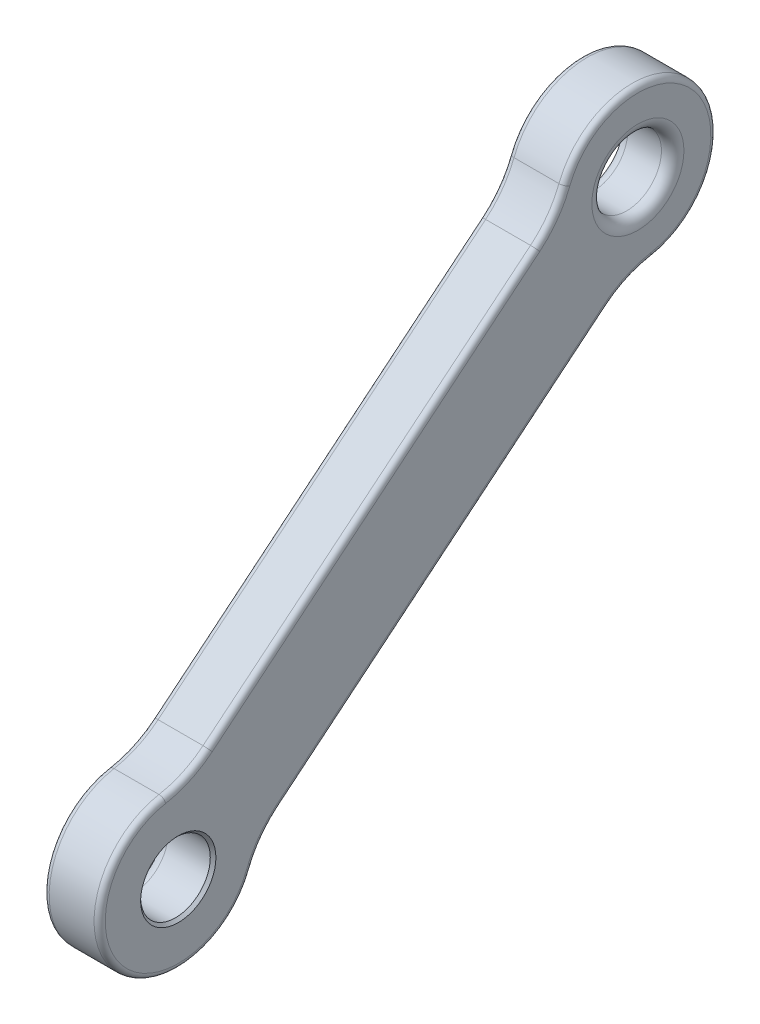
SolidWorks part; units mm, degrees
material "ABS"
ref_plane "Front Plane" through (0, 0, 0) normal (1, 0, 0) x (0, 1, 0)
ref_plane "Top Plane" through (0, 0, 0) normal (0, 0, 1) x (0, 1, 0)
ref_plane "Right Plane" through (0, 0, 0) normal (0, 1, 0) x (-1, 0, 0)
sketch "Sketch1" plane through (0, 0, 0) normal (1, 0, 0) x (0, 1, 0)
  line L0 (-11.6048, -20) -> (24.9519, -20)
  line L1 (84.9519, 40) -> (84.9519, 57.8005)
  line L4 (-38.5328, 56.8878) -> (-47.7982, 43.6554)
  line L5 (64.9519, 37.5) -> (87.5414, -36.1119)
  line L6 (87.5414, -36.1119) -> (67.3498, -81.8536)
  line L7 (67.3498, -81.8536) -> (4.2234, -204.9062)
  line L8 (67.3498, -81.8536) -> (0, 0)
  line L9 (0, 0) -> (64.9519, 37.5) construction
  line L11 (-49.5322, 36.7009) -> (-46.3439, 10.7346)
  line L12 (-32.0778, 61.0001) -> (61.4789, 77.4967)
  arc A0 (24.9519, -20) -> (84.9519, 40) centre (24.9519, 40) ccw
  arc A1 (84.9519, 57.8005) -> (61.4789, 77.4967) centre (64.9519, 57.8005) ccw
  circle A3 centre (0, 0) radius 5
  circle A4 centre (0, 0) radius 10
  circle A5 centre (64.9519, 37.5) radius 5
  circle A6 centre (64.9519, 37.5) radius 10
  circle A7 centre (87.5414, -36.1119) radius 5
  circle A8 centre (87.5414, -36.1119) radius 10
  circle A9 centre (67.3498, -81.8536) radius 5
  circle A10 centre (67.3498, -81.8536) radius 10
  circle A11 centre (4.2234, -204.9062) radius 10
  circle A12 centre (4.2234, -204.9062) radius 50
  arc A13 (-46.3439, 10.7346) -> (-11.6048, -20) centre (-11.6048, 15) ccw
  arc A14 (-47.7982, 43.6554) -> (-49.5322, 36.7009) centre (-39.6067, 37.9196) ccw
  arc A16 (-32.0778, 61.0001) -> (-38.5328, 56.8878) centre (-30.3413, 51.152) ccw
  dimension "D3" = 60
  dimension "D16" = 20
  dimension "D17" = 10
  dimension "D18" = 20
  dimension "D19" = 100
  dimension "D22" = 35
  dimension "D24" = 10
  dimension "D7" = 10
  dimension "D1" = 20
  dimension "D4" = 20
  dimension "D5" = 95
  dimension "D9" = 10
  dimension "D10" = 75
  dimension "D11" = 77
  dimension "D12" = 50
  dimension "D13" = 138.3
  dimension "D14" = 3.34
  dimension "D15" = 30
  dimension "D20" = 106
sketch "Sketch2" plane through (0, 0, 0) normal (1, 0, 0) x (0, 1, 0)
  line L1 (65.3941, -63.738) -> (17.3998, -5.4081)
  line L2 (0, 0) -> (67.3498, -81.8536) construction
  line L3 (1.9557, -18.1156) -> (49.95, -76.4455)
  circle A0 centre (0, 0) radius 10 construction
  circle A1 centre (67.3498, -81.8536) radius 10 construction
  arc A2 (7.722, 6.3538) -> (-7.722, -6.3538) centre (0, 0) ccw construction
  arc A3 (59.6277, -88.2073) -> (59.0267, -87.3968) centre (67.3498, -81.8536) ccw construction
  circle A6 centre (0, 0) radius 6.2
  circle A7 centre (67.3498, -81.8536) radius 6.2
  arc A8 (13.7865, 2.4357) -> (-5.0453, -13.0593) centre (0, 0) ccw
  arc A9 (53.5633, -84.2892) -> (72.3951, -68.7943) centre (67.3498, -81.8536) ccw
  arc A10 (65.3941, -63.738) -> (72.3951, -68.7943) centre (78.5215, -52.9366) ccw
  arc A11 (13.7865, 2.4357) -> (17.3998, -5.4081) centre (30.5272, 5.3933) ccw
  arc A14 (-5.0453, -13.0593) -> (1.9557, -18.1156) centre (-11.1717, -28.917) cw
  arc A15 (49.95, -76.4455) -> (53.5633, -84.2892) centre (36.8225, -87.2469) cw
  dimension "D1" = 28
  dimension "D2" = 17
  dimension "D3" = 12.4
extrude "Boss-Extrude1" add sketch "Sketch2" along normal blind 10
fillet "Fillet1" radius 1 16 edges at (0, 41.3969, -34.573) (10, 41.3969, -34.573) (0, 15.0868, -1.7195) (0, -8.8953, 10.8108) (0, -1.2184, -15.1355) (0, 25.9529, -47.2805) (0, 52.263, -80.1341) (0, 76.245, -92.6644) (0, 68.5681, -66.7181) (10, 76.245, -92.6644) (10, 52.263, -80.1341) (10, 25.9529, -47.2805) (10, -1.2184, -15.1355) (10, -8.8953, 10.8108) (10, 15.0868, -1.7195) (10, 68.5681, -66.7181)
fillet "Fillet2" radius 2 3 edges at (0, 67.3498, -88.0536) (10, 67.3498, -88.0536) (0, 0, -6.2)
chamfer "Chamfer1" distance 0.5 angle 45 1 edges at (10, 0, -6.2)
sketch "Sketch3" plane through (0, 0, 0) normal (-1, 0, 0) x (0, -1, 0)
  line L0 (-65.29, -76.0057) -> (-64.1463, -74.6158)
  line L1 (-63.8648, -74.5884) -> (-60.8918, -77.0346)
  line L2 (-60.8644, -77.3161) -> (-62.0081, -78.7061)
  line L3 (-72.6914, -85.0011) -> (-73.8351, -86.391)
  line L4 (-73.8077, -86.6726) -> (-70.8348, -89.1188)
  line L5 (-70.5532, -89.0914) -> (-69.4096, -87.7014)
  line L7 (-67.3498, -81.8536) -> (-72.3212, -87.8957) construction
  line L8 (-67.3498, -81.8536) -> (0, 0) construction
  circle A0 centre (-67.3498, -81.8536) radius 6.2 construction
  arc A1 (-72.6914, -85.0011) -> (-69.4096, -87.7014) centre (-67.3498, -81.8536) ccw
  arc A2 (-62.0081, -78.7061) -> (-65.29, -76.0057) centre (-67.3498, -81.8536) ccw
  arc A7 (-73.8077, -86.6726) -> (-73.8351, -86.391) centre (-73.6807, -86.5181) cw
  arc A8 (-70.8348, -89.1188) -> (-70.5532, -89.0914) centre (-70.7077, -88.9643) ccw
  arc A9 (-64.1463, -74.6158) -> (-63.8648, -74.5884) centre (-63.9919, -74.7428) cw
  arc A10 (-60.8918, -77.0346) -> (-60.8644, -77.3161) centre (-61.0189, -77.189) cw
  point P11 (-62.3783, -75.8115)
  point P17 (-64.0192, -74.4613)
  point P24 (-60.7374, -77.1617)
  dimension "D3" = 0.2
  dimension "D1" = 4.25
  dimension "D2" = 2
extrude "Cut-Extrude1" cut sketch "Sketch3" against normal blind 3
fillet "Fillet3" radius 0.2 26 edges at (2.5, 69.4096, -87.7014) (0.6716, 69.7494, -88.1144) (2.5, 62.0081, -78.7061) (0.8029, 61.7401, -78.3804) (2.5, 72.6914, -85.0011) (0.8029, 72.9594, -85.3268) (3, 69.9814, -88.3964) (3, 72.3212, -87.8957) (3, 73.2633, -85.6961) (3, 71.2891, -86.6412) (2.5, 65.29, -76.0057) (0.6716, 64.9502, -75.5928) (3, 64.7182, -75.3107) (3, 62.3783, -75.8115) (3, 61.4363, -78.0111) (3, 63.4104, -77.0659) (0.0059, 70.711, -89.1643) (0.0078, 73.8806, -86.5148) (0.0078, 60.8189, -77.1923) (0.0059, 63.9885, -74.5429) (3, 70.6883, -89.1634) (3, 73.8797, -86.5375) (3, 64.0112, -74.5438) (3, 60.8198, -77.1697)
